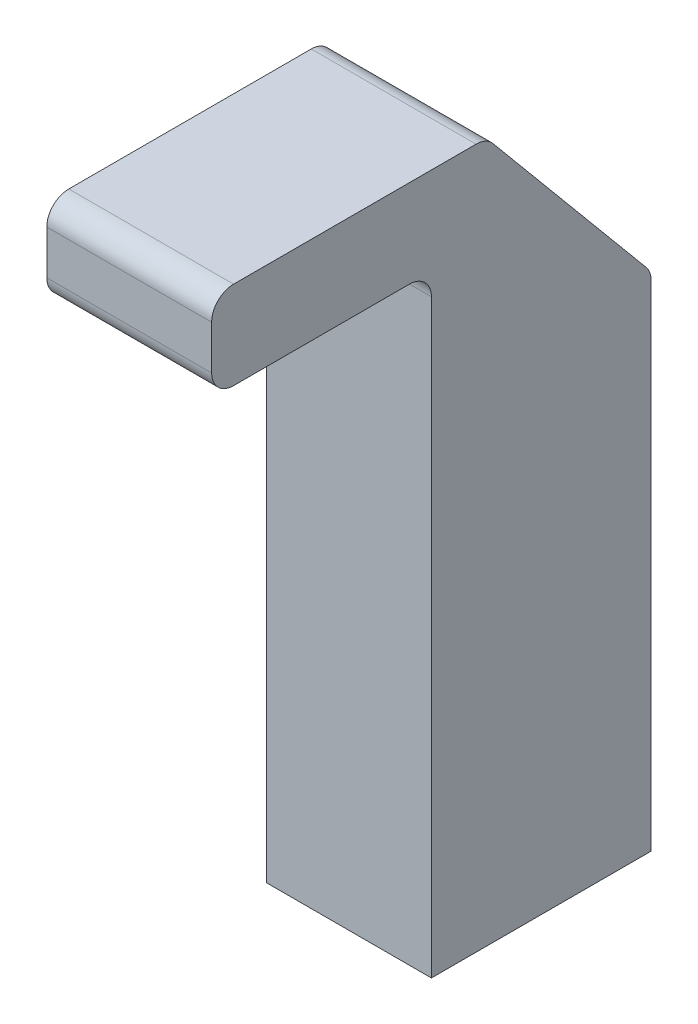
SolidWorks part; units mm, degrees
ref_plane "Front Plane" through (0, 0, 0) normal (0, 0, 1) x (1, 0, 0)
ref_plane "Top Plane" through (0, 0, 0) normal (0, 1, 0) x (1, 0, 0)
ref_plane "Right Plane" through (0, 0, 0) normal (1, 0, 0) x (0, 0, -1)
sketch "Sketch1" plane through (0, 0, 0) normal (1, 0, 0) x (0, 0, -1)
  line L0 (0, 0) -> (0, 8)
  line L1 (0, 8) -> (25, 8)
  line L4 (40, -10) -> (40, -55.68)
  line L5 (40, -55.68) -> (20, -55.68)
  line L6 (20, -55.68) -> (20, 0)
  line L7 (20, 0) -> (0, 0)
  line L8 (25, 8) -> (40, -10)
  dimension "D1" = 55.68
  dimension "D2" = 8
  dimension "D3" = 20
  dimension "D4" = 25
  dimension "D5" = 20
  dimension "D6" = 45.68
extrude "Boss-Extrude1" add sketch "Sketch1" along normal mid plane 15
sketch "Sketch2" plane through (0, 8, 0) normal (0, 1, 0) x (1, 0, 0)
  line L0 (-7.5, 40) -> (-7.5, 25) construction
  line L1 (7.5, 40) -> (7.5, 25) construction
  line L2 (7.5, 25) -> (-7.5, 25) construction
  circle A0 centre (-4, 31) radius 2
  circle A1 centre (4, 31) radius 2
  dimension "D1" = 4
  dimension "D2" = 4
  dimension "D6" = 6
  dimension "D3" = 3.5
  dimension "D4" = 3.5
  dimension "D5" = 6
extrude "Cut-Extrude1" cut sketch "Sketch2" against normal offset from surface (58.68 mm away) 5 up to face at (0, -55.68, -30)
sketch "Sketch3" plane through (0, 8, 0) normal (0, 1, 0) x (1, 0, 0)
  circle A0 centre (-4, 31) radius 1.05
  circle A1 centre (4, 31) radius 1.05
  dimension "D1" = 2.1
  dimension "D2" = 2.1
extrude "Cut-Extrude2" cut sketch "Sketch3" against normal up to next
fillet "Fillet1" radius 2 5 edges at (0, -10, -40) (0, 8, -25) (0, 8, 0) (0, 0, 0) (0, 0, -20)
